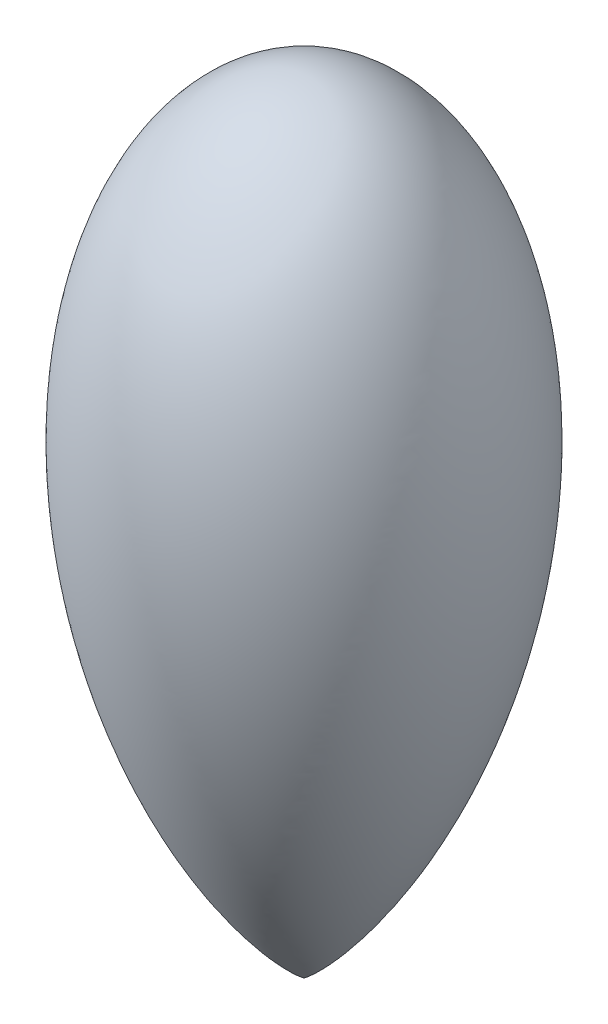
SolidWorks part; units mm, degrees
ref_plane "Front Plane" through (0, 0, 0) normal (0, 0, 1) x (1, 0, 0)
ref_plane "Top Plane" through (0, 0, 0) normal (0, 1, 0) x (1, 0, 0)
ref_plane "Right Plane" through (0, 0, 0) normal (1, 0, 0) x (0, 0, -1)
sketch "Sketch" plane through (0, 0, 0) normal (0, 0, 1) x (1, 0, 0)
  line L0 (0, 397.8874) -> (0, 0) construction
  line L1 (0, 397.8874) -> (0, 0)
  spline S0 degree 4 poles (-36.9242, 385.3358) (-35.9025, 386.0641) (-34.3472, 387.1244) (-32.228, 388.4702) (-29.515, 390.0245) (-27.3136, 391.1851) (-25.0814, 392.2611) (-22.8208, 393.2501) (-20.5244, 394.1529) (-18.4858, 394.8644) (-16.7195, 395.4159) (-15.2358, 395.8358) (-14.0424, 396.1474) (-12.8424, 396.4344) (-11.6376, 396.6965) (-10.1233, 396.9925) (-8.604, 397.2459) (-7.0736, 397.456) (-5.2384, 397.6557) (-3.8469, 397.7659) (-2.6284, 397.8327) (-1.5312, 397.8678) (-0.9537, 397.8812) (-0.2494, 397.8879) (0.2519, 397.8879) (0.9604, 397.8812) (1.5351, 397.8677) (2.3317, 397.8423) (3.2468, 397.7984) (4.3376, 397.7276) (5.5674, 397.6199) (6.8026, 397.4854) (8.03, 397.3245) (9.2563, 397.1373) (10.4769, 396.924) (11.9975, 396.6252) (13.8112, 396.2155) (15.9099, 395.6647) (18.2806, 394.938) (20.6205, 394.1174) (22.9266, 393.2063) (25.1965, 392.2083) (27.9857, 390.857) (31.2524, 389.0767) (34.6558, 386.9615) (38.1626, 384.4867) (41.2785, 382.0471) (44.0348, 379.6954) (46.7122, 377.2189) (49.3095, 374.6243) (52.4587, 371.2371) (56.0615, 366.9757) (59.9872, 361.7807) (64.3011, 355.3013) (68.4056, 348.2866) (72.1116, 341.0536) (75.4438, 333.6424) (78.3159, 326.4098) (80.7881, 319.3939) (83.0003, 312.292) (84.9646, 305.1177) (87.1237, 296.0742) (89.2609, 285.1213) (91.1324, 272.2353) (92.4788, 257.4159) (93.0832, 242.5486) (92.9633, 223.9502) (91.4893, 201.6716) (87.9566, 175.8545) (82.3851, 150.4015) (76.2138, 128.9478) (70.1533, 111.366) (64.7556, 97.502) (58.806, 83.8655) (52.297, 70.4867) (46.1002, 59.0372) (40.4167, 49.4354) (35.4215, 41.5942) (31.2645, 35.4266) (27.1151, 29.6215) (22.9873, 24.1759) (19.3818, 19.6937) (16.3642, 16.1278) (13.7853, 13.212) (11.6813, 10.9163) (9.5816, 8.7123) (7.7354, 6.8536) (6.1585, 5.3261) (4.8657, 4.1156) (3.818, 3.1618) (2.7552, 2.2248) (1.8099, 1.4225) (1.0548, 0.8071) (0.497, 0.3705) (0.2146, 0.1566) (0.0718, 0.0519) (0, 0) knots 0 0 0 0 0 0.009945 0.014918 0.01989 0.024779 0.029667 0.034556 0.039445 0.044333 0.046777 0.049222 0.051666 0.05411 0.056555 0.058999 0.063887 0.066332 0.068776 0.073665 0.074887 0.076109 0.077331 0.078553 0.079781 0.081009 0.082237 0.083466 0.085922 0.088378 0.090834 0.09329 0.095747 0.098203 0.100659 0.103115 0.108028 0.11294 0.117853 0.122765 0.127678 0.13259 0.137503 0.147328 0.157152 0.16433 0.171508 0.178686 0.185864 0.193233 0.200602 0.215339 0.230077 0.244814 0.26227 0.279726 0.294464 0.309201 0.323938 0.338676 0.353413 0.368151 0.397626 0.4271 0.456575 0.48605 0.515525 0.574475 0.633425 0.692374 0.721849 0.751324 0.780799 0.810274 0.839749 0.869223 0.883961 0.898698 0.913436 0.928173 0.940515 0.952856 0.959027 0.965197 0.971368 0.977539 0.983154 0.985962 0.988769 0.991577 0.994385 0.997192 0.998596 0.999298 1 1 1 1 1 construction
  spline S1 degree 4 poles (0, 397.8874) (0.1428, 397.8874) (0.4284, 397.8862) (0.9604, 397.8812) (1.5351, 397.8677) (2.3317, 397.8423) (3.2468, 397.7984) (4.3376, 397.7276) (5.5674, 397.6199) (6.8026, 397.4854) (8.03, 397.3245) (9.2563, 397.1373) (10.4769, 396.924) (11.9975, 396.6252) (13.8112, 396.2155) (15.9099, 395.6647) (18.2806, 394.938) (20.6205, 394.1174) (22.9266, 393.2063) (25.1965, 392.2083) (27.9857, 390.857) (31.2524, 389.0767) (34.6558, 386.9615) (38.1626, 384.4867) (41.2785, 382.0471) (44.0348, 379.6954) (46.7122, 377.2189) (49.3095, 374.6243) (52.4587, 371.2371) (56.0615, 366.9757) (59.9872, 361.7807) (64.3011, 355.3013) (68.4056, 348.2866) (72.1116, 341.0536) (75.4438, 333.6424) (78.3159, 326.4098) (80.7881, 319.3939) (83.0003, 312.292) (84.9646, 305.1177) (87.1237, 296.0742) (89.2609, 285.1213) (91.1324, 272.2353) (92.4788, 257.4159) (93.0832, 242.5486) (92.9633, 223.9502) (91.4893, 201.6716) (87.9566, 175.8545) (82.3851, 150.4015) (76.2138, 128.9478) (70.1533, 111.366) (64.7556, 97.502) (58.806, 83.8655) (52.297, 70.4867) (46.1002, 59.0372) (40.4167, 49.4354) (35.4215, 41.5942) (31.2645, 35.4266) (27.1151, 29.6215) (22.9873, 24.1759) (19.3818, 19.6937) (16.3642, 16.1278) (13.7853, 13.212) (11.6813, 10.9163) (9.5816, 8.7123) (7.7354, 6.8536) (6.1585, 5.3261) (4.8657, 4.1156) (3.818, 3.1618) (2.7552, 2.2248) (1.8099, 1.4225) (1.0548, 0.8071) (0.497, 0.3705) (0.2146, 0.1566) (0.0718, 0.0519) (0, 0) knots 0.078553 0.078553 0.078553 0.078553 0.078553 0.079781 0.081009 0.082237 0.083466 0.085922 0.088378 0.090834 0.09329 0.095747 0.098203 0.100659 0.103115 0.108028 0.11294 0.117853 0.122765 0.127678 0.13259 0.137503 0.147328 0.157152 0.16433 0.171508 0.178686 0.185864 0.193233 0.200602 0.215339 0.230077 0.244814 0.26227 0.279726 0.294464 0.309201 0.323938 0.338676 0.353413 0.368151 0.397626 0.4271 0.456575 0.48605 0.515525 0.574475 0.633425 0.692374 0.721849 0.751324 0.780799 0.810274 0.839749 0.869223 0.883961 0.898698 0.913436 0.928173 0.940515 0.952856 0.959027 0.965197 0.971368 0.977539 0.983154 0.985962 0.988769 0.991577 0.994385 0.997192 0.998596 0.999298 1 1 1 1 1
revolve "Revolve" add sketch "Sketch" angle 360 about L0
